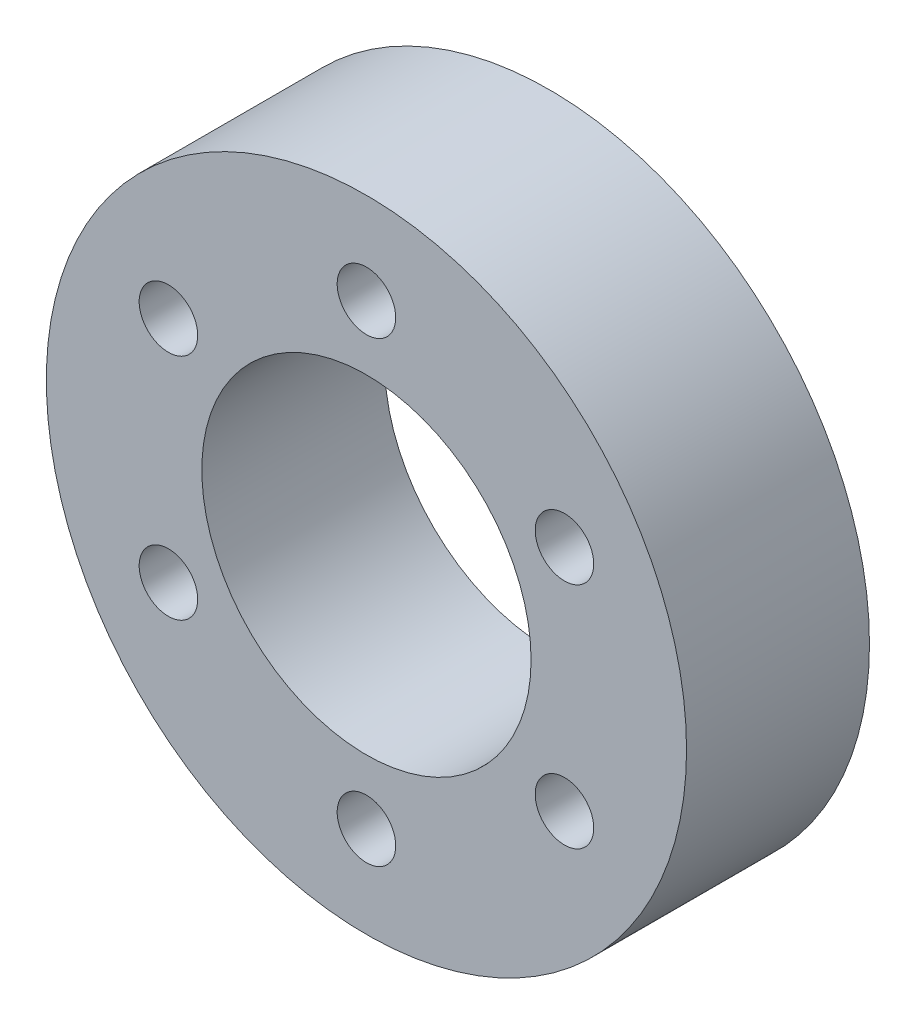
SolidWorks part; units mm, degrees
material "Custom Plastic"
ref_plane "Front Plane" through (0, 0, 0) normal (0, 0, 1) x (1, 0, 0)
ref_plane "Top Plane" through (0, 0, 0) normal (0, 1, 0) x (1, 0, 0)
ref_plane "Right Plane" through (0, 0, 0) normal (1, 0, 0) x (0, 0, -1)
sketch "Sketch1" plane through (0, 0, 0) normal (0, 0, 1) x (1, 0, 0)
  line L0 (0, 0) -> (0, 12.5) construction
  circle A0 centre (0, 0) radius 17.5
  circle A1 centre (0, 12.5) radius 1.6
  circle A2 centre (10.8253, 6.25) radius 1.6
  circle A3 centre (10.8253, -6.25) radius 1.6
  circle A4 centre (0, -12.5) radius 1.6
  circle A5 centre (-10.8253, -6.25) radius 1.6
  circle A6 centre (-10.8253, 6.25) radius 1.6
  circle A7 centre (0, 0) radius 9
  point P17 (0, 0)
  dimension "D1" = 35
  dimension "D3" = 3.2
  dimension "D5" = 18
  dimension "D2" = 12.5
  dimension "D4" = 6
extrude "Boss-Extrude1" add sketch "Sketch1" along normal blind 10
